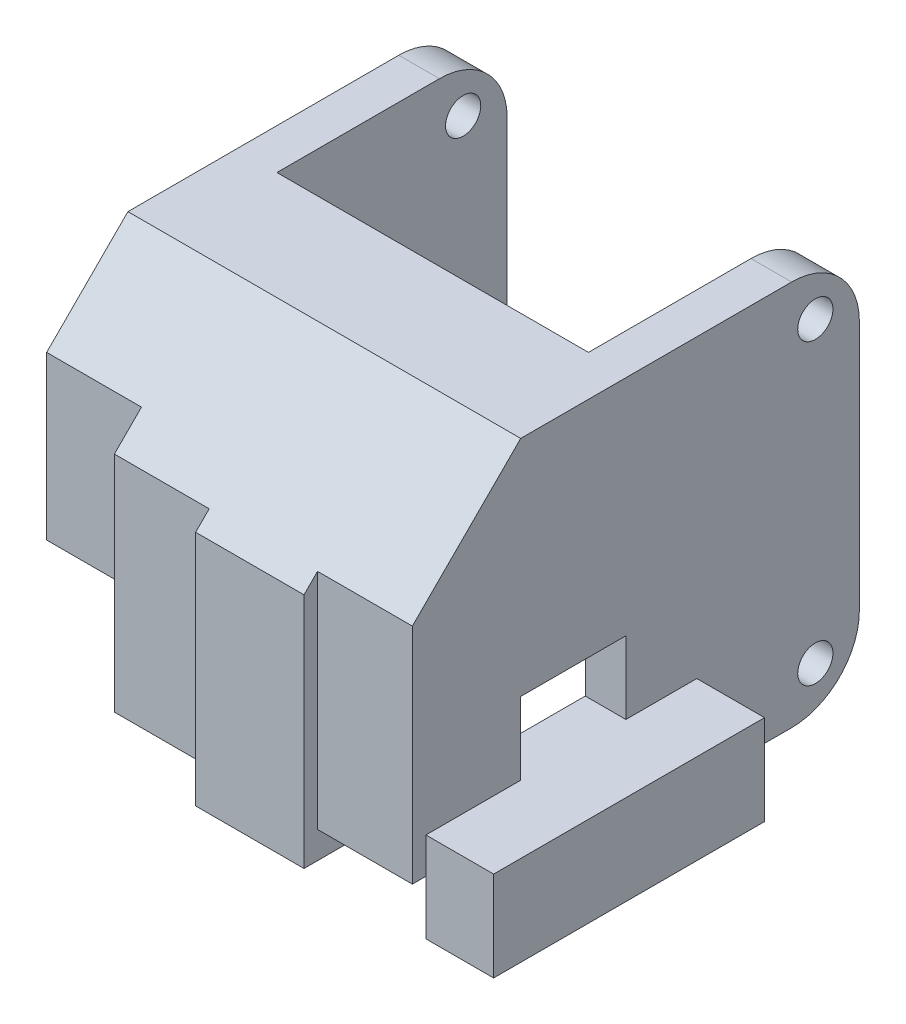
SolidWorks part; units mm, degrees
ref_plane "Front Plane" through (0, 0, 0) normal (0, 0, 1) x (1, 0, 0)
ref_plane "Top Plane" through (0, 0, 0) normal (0, 1, 0) x (1, 0, 0)
ref_plane "Right Plane" through (0, 0, 0) normal (1, 0, 0) x (0, 0, -1)
sketch "Sketch1" plane through (0, 0, 0) normal (0, 0, 1) x (1, 0, 0)
  line L1 (-14.5, 14.25) -> (14.5, 14.25)
  line L2 (-14.5, 14.25) -> (-14.5, -14.25)
  line L3 (-14.5, -14.25) -> (14.5, -14.25)
  line L4 (14.5, 14.25) -> (14.5, -14.25)
  line L5 (-14.5, 14.25) -> (14.5, -14.25) construction
  line L6 (-14.5, -14.25) -> (14.5, 14.25) construction
  point P0 (0, 0)
  dimension "D1" = 29
  dimension "D2" = 28.5
extrude "Boss-Extrude1" add sketch "Sketch1" along normal blind 25
sketch "Sketch2" plane through (14.5, 0, 0) normal (1, 0, 0) x (0, 0, -1)
  line L2 (-25, 14.25) -> (0, 14.25) construction
  line L3 (0, -14.25) -> (0, 14.25) construction
  circle A0 centre (-3.25, 11) radius 1.3
  circle A1 centre (-3.25, -11) radius 1.3
  dimension "D1" = 2.6
  dimension "D2" = 3.25
  dimension "D3" = 3.25
  dimension "D6" = 22
  dimension "D4" = 2
extrude "Cut-Extrude1" cut sketch "Sketch2" against normal through all
fillet "Fillet1" radius 5 2 edges at (0, -14.25, 0) (0, 14.25, 0)
sketch "Sketch3" plane through (0, 0, 0) normal (0, 0, -1) x (-1, 0, 0)
  line L0 (-14.5, 14.25) -> (14.5, 14.25) construction
  line L1 (-11.5, 14.25) -> (11.5, 14.25)
  line L2 (-11.5, 14.25) -> (-11.5, -14.25)
  line L3 (-11.5, -14.25) -> (11.5, -14.25)
  line L4 (11.5, 14.25) -> (11.5, -14.25)
  line L5 (14.5, -14.25) -> (-14.5, -14.25) construction
  line L6 (14.5, 9.25) -> (14.5, -9.25) construction
  dimension "D1" = 3
  dimension "D2" = 3
extrude "Cut-Extrude2" cut sketch "Sketch3" against normal blind 17
sketch "Sketch5" plane through (0, 0, 25) normal (0, 0, 1) x (1, 0, 0)
  line L0 (-14.5, -14.25) -> (14.5, -14.25) construction
  line L1 (-14.5, 14.25) -> (-7.5, 14.25)
  line L2 (-14.5, 14.25) -> (-14.5, -3.75)
  line L3 (-14.5, -3.75) -> (-7.5, -3.75)
  line L4 (-7.5, 14.25) -> (-7.5, -3.75)
  line L5 (-7.5, 14.25) -> (-0.5, 14.25)
  line L6 (-7.5, 14.25) -> (-7.5, -10.25)
  line L7 (-7.5, -10.25) -> (-0.5, -10.25)
  line L8 (-0.5, 14.25) -> (-0.5, -10.25)
  line L9 (-0.5, 14.25) -> (7.5, 14.25)
  line L10 (-0.5, 14.25) -> (-0.5, -10.25)
  line L12 (7.5, 14.25) -> (7.5, -10.25)
  line L13 (14.5, -14.25) -> (14.5, 14.25) construction
  line L14 (7.5, 14.25) -> (14.5, 14.25)
  line L15 (7.5, 14.25) -> (7.5, -10.25)
  line L16 (7.5, -10.25) -> (14.5, -10.25)
  line L17 (14.5, 14.25) -> (14.5, -10.25)
  line L19 (-0.5, 14.25) -> (7.5, 14.25)
  line L20 (-0.5, 14.25) -> (-0.5, -12.25)
  line L21 (-0.5, -12.25) -> (7.5, -12.25)
  line L22 (7.5, 14.25) -> (7.5, -12.25)
  line M6 (14.5, 14.25) -> (-14.5, 14.25)
  line M7 (-14.5, 14.25) -> (-14.5, -14.25)
  dimension "D1" = 7
  dimension "D2" = 7
  dimension "D3" = 2
  dimension "D4" = 18
  dimension "D5" = 4
  dimension "D6" = 4
extrude "Boss-Extrude2" add sketch "Sketch5" along normal blind 6 contours L4 L3 M6 M7
sketch "Sketch6" plane through (0, 0, 25) normal (0, 0, 1) x (1, 0, 0)
  line L1 (-7.5, 14.25) -> (-0.5, 14.25)
  line L2 (-7.5, 14.25) -> (-7.5, -10.25)
  line L4 (-0.5, 14.25) -> (-0.5, -10.25)
  line L5 (-7.5, -10.25) -> (-0.5, -10.25)
  line L6 (-14.5, -14.25) -> (14.5, -14.25) construction
  dimension "D1" = 7
  dimension "D2" = 4
extrude "Boss-Extrude3" add sketch "Sketch6" along normal blind 8
sketch "Sketch8" plane through (0, 0, 25) normal (0, 0, 1) x (1, 0, 0)
  line L0 (-14.5, -14.25) -> (14.5, -14.25) construction
  line L1 (-0.5, 14.25) -> (7.5, 14.25)
  line L2 (-0.5, 14.25) -> (-0.5, -12.25)
  line L3 (-0.5, -12.25) -> (7.5, -12.25)
  line L4 (7.5, 14.25) -> (7.5, -12.25)
  dimension "D1" = 2
  dimension "D2" = 8
extrude "Boss-Extrude4" add sketch "Sketch8" along normal blind 9
sketch "Sketch9" plane through (0, 0, 25) normal (0, 0, 1) x (1, 0, 0)
  line L0 (7.5, -12.25) -> (7.5, 14.25) construction
  line L1 (14.5, 14.25) -> (7.5, 14.25)
  line L2 (14.5, 14.25) -> (14.5, -10.25)
  line L3 (14.5, -10.25) -> (7.5, -10.25)
  line L4 (7.5, 14.25) -> (7.5, -10.25)
extrude "Boss-Extrude5" add sketch "Sketch9" along normal blind 8
sketch "Sketch10" plane through (14.5, 0, 0) normal (1, 0, 0) x (0, 0, -1)
  line L0 (-25, -14.25) -> (-25, 14.25)
  line L1 (-33, 14.25) -> (-5, 14.25) construction
  line L2 (-25, 14.25) -> (-34, 5.25)
  line L3 (-34, -12.25) -> (-34, 14.25) construction
  line L4 (-34, 5.25) -> (-34, 14.25)
  line L5 (-34, 14.25) -> (-25, 14.25)
  line L6 (-25, -12.25) -> (-34, -4.1045)
  line L7 (-25, -14.25) -> (-25, -10.25) construction
  line L8 (-34, -4.1045) -> (-34, -12.25)
  line L9 (-34, -12.25) -> (-25, -12.25)
  line M7 (-5, 14.25) -> (-33, 14.25)
  line M8 (-33, 14.25) -> (-33, -10.25)
extrude "Cut-Extrude5" cut sketch "Sketch10" against normal blind 31 contours L2 M7 M8 | L5 L4 L2 M8
sketch "Sketch11" plane through (14.5, 0, 0) normal (1, 0, 0) x (0, 0, -1)
  line L0 (-25, -14.25) -> (-5, -14.25) construction
  line L1 (-12, -14.25) -> (-32, -14.25)
  line L2 (-12, -14.25) -> (-12, -7.6041)
  line L3 (-12, -7.6041) -> (-32, -7.6041)
  line L4 (-32, -14.25) -> (-32, -7.6041)
  line L5 (0, -9.25) -> (0, 9.25) construction
  dimension "D1" = 20
  dimension "D2" = 12
extrude "Boss-Extrude6" add sketch "Sketch11" along normal blind 5
sketch "Sketch14" plane through (-14.5, 0, 0) normal (-1, 0, 0) x (0, 0, 1)
  line L1 (25, -14.25) -> (10, -14.25)
  line L2 (25, -14.25) -> (25, -2.25)
  line L3 (25, -2.25) -> (10, -2.25)
  line L4 (10, -14.25) -> (10, -2.25)
  dimension "D1" = 15
  dimension "D2" = 12
extrude "Cut-Extrude8" cut sketch "Sketch14" against normal blind 26
sketch "Sketch15" plane through (11.5, 0, 0) normal (-1, 0, 0) x (0, 0, 1)
  line L0 (12, -7.6041) -> (32, -7.6041) construction
  line L1 (25, -2.25) -> (17.2356, -2.25)
  line L2 (25, -2.25) -> (25, -7.6041)
  line L3 (25, -7.6041) -> (17.2356, -7.6041)
  line L4 (17.2356, -2.25) -> (17.2356, -7.6041)
extrude "Cut-Extrude9" cut sketch "Sketch15" against normal blind 25
sketch "Sketch16" plane through (-14.5, 0, 0) normal (-1, 0, 0) x (0, 0, 1)
  line L1 (25, -2.25) -> (10, -2.25)
  line L2 (25, -2.25) -> (25, 1.75)
  line L3 (25, 1.75) -> (10, 1.75)
  line L4 (10, -2.25) -> (10, 1.75)
  dimension "D1" = 4
  dimension "D2" = 15
extrude "Cut-Extrude11" cut sketch "Sketch16" against normal blind 26
